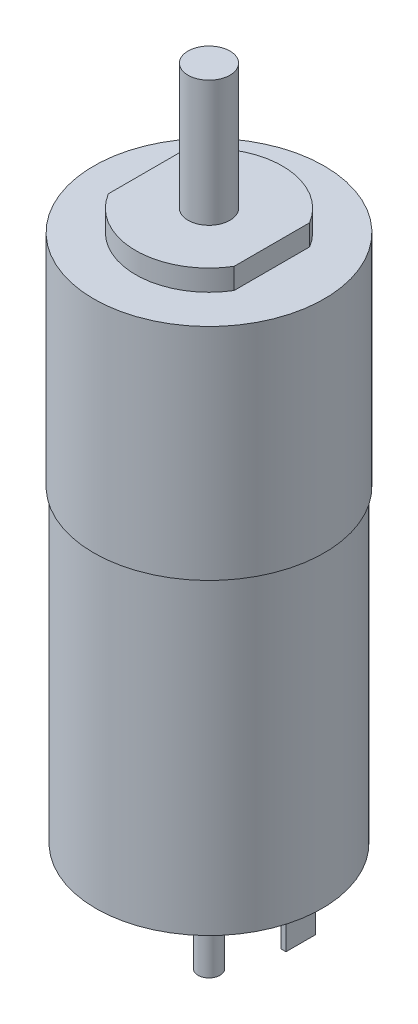
SolidWorks part; units mm, degrees
ref_plane "Front Plane" through (0, 0, 0) normal (0, 0, 1) x (1, 0, 0)
ref_plane "Top Plane" through (0, 0, 0) normal (0, 1, 0) x (1, 0, 0)
ref_plane "Right Plane" through (0, 0, 0) normal (1, 0, 0) x (0, 0, -1)
sketch "Sketch2" plane through (0, 0, 0) normal (0, 1, 0) x (1, 0, 0)
  circle A0 centre (0, 0) radius 10.8
  dimension "D1" = 21.6
extrude "Boss-Extrude1" add sketch "Sketch2" along normal blind 29.5
sketch "Sketch3" plane through (0, 29.5, 0) normal (0, 1, 0) x (1, 0, 0)
  circle A0 centre (0, 0) radius 11
  dimension "D1" = 22
extrude "Boss-Extrude2" add sketch "Sketch3" along normal blind 21
sketch "Sketch4" plane through (0, 50.5, 0) normal (0, 1, 0) x (1, 0, 0)
  line L0 (-6, 0) -> (6, 0) construction
  line L1 (6, 3.6056) -> (6, -3.6056)
  line L2 (-6, 3.6056) -> (-6, -3.6056)
  arc A0 (-6, -3.6056) -> (6, -3.6056) centre (0, 0) ccw
  arc A1 (6, 3.6056) -> (-6, 3.6056) centre (0, 0) ccw
  point P9 (0, 0)
  dimension "D1" = 14
  dimension "D2" = 12
extrude "Boss-Extrude3" add sketch "Sketch4" along normal blind 2
sketch "Sketch5" plane through (0, 52.5, 0) normal (0, 1, 0) x (1, 0, 0)
  circle A0 centre (0, 0) radius 2
  dimension "D1" = 4
extrude "Boss-Extrude4" add sketch "Sketch5" along normal blind 12
sketch "Sketch6" plane through (0, 0, 0) normal (0, -1, 0) x (1, 0, 0)
  circle A0 centre (0, 0) radius 3.75
  dimension "D1" = 7.5
extrude "Boss-Extrude5" add sketch "Sketch6" along normal blind 2
sketch "Sketch7" plane through (0, 0, 0) normal (0, -1, 0) x (1, 0, 0)
  line L0 (-8.25, 0) -> (8.25, 0) construction
  line L1 (-8.75, 1.4) -> (-8.25, 1.4)
  line L2 (-8.75, 1.4) -> (-8.75, -1.4)
  line L3 (-8.75, -1.4) -> (-8.25, -1.4)
  line L4 (-8.25, 1.4) -> (-8.25, -1.4)
  line L5 (8.25, 1.4) -> (8.75, 1.4)
  line L6 (8.25, 1.4) -> (8.25, -1.4)
  line L7 (8.25, -1.4) -> (8.75, -1.4)
  line L8 (8.75, 1.4) -> (8.75, -1.4)
  point P8 (8.75, 0)
  point P12 (0, 0)
  dimension "D1" = 2.8
  dimension "D2" = 0.5
  dimension "D3" = 16.5
extrude "Boss-Extrude6" add sketch "Sketch7" along normal blind 3.9
sketch "Sketch8" plane through (0, -2, 0) normal (0, -1, 0) x (1, 0, 0)
  circle A0 centre (0, 0) radius 1.05
  dimension "D1" = 2.1
extrude "Boss-Extrude7" add sketch "Sketch8" along normal blind 8.4
